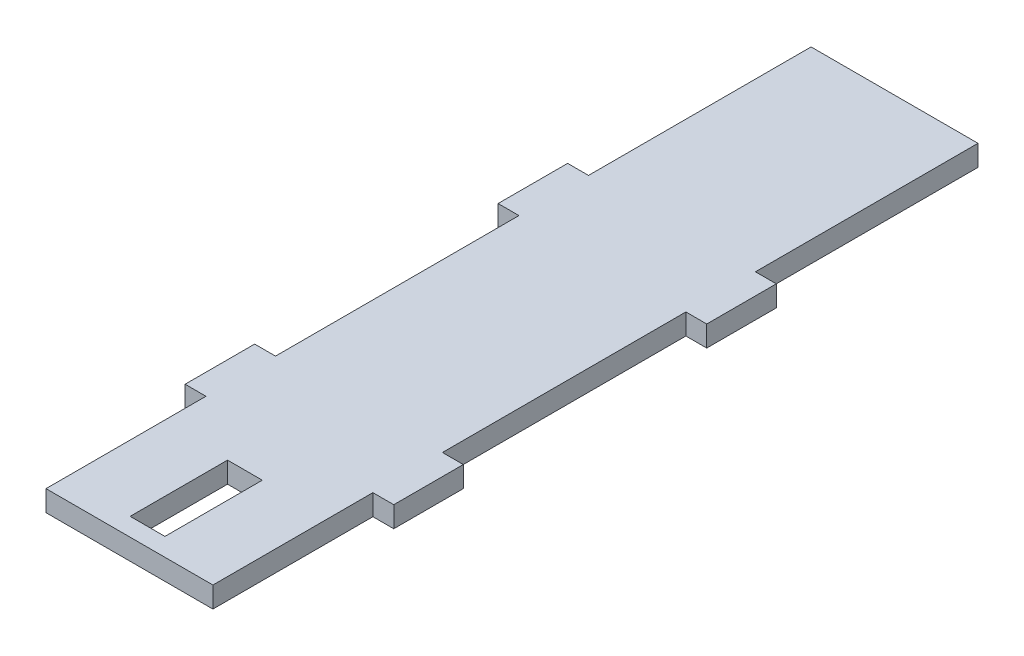
SolidWorks part; units mm, degrees
ref_plane "Спереди" through (0, 0, 0) normal (0, 0, 1) x (1, 0, 0)
ref_plane "Сверху" through (0, 0, 0) normal (0, 1, 0) x (1, 0, 0)
ref_plane "Справа" through (0, 0, 0) normal (1, 0, 0) x (0, 0, -1)
other "Configuration Table"
sketch "Эскиз1" plane through (0, 0, 0) normal (0, 1, 0) x (1, 0, 0)
  line L0 (0, -24.7852) -> (0, 24.7852) construction
  line L1 (-12, -55) -> (12, -55)
  line L2 (-12, -55) -> (-12, -32)
  line L3 (-12, 55) -> (12, 55)
  line L4 (12, -55) -> (12, -32)
  line L5 (-12, -55) -> (12, 55) construction
  line L6 (-12, 55) -> (12, -55) construction
  line L7 (12, -22) -> (15, -22)
  line L9 (12, -32) -> (15, -32)
  line L10 (15, -22) -> (15, -32)
  line L11 (-19.5061, 0) -> (19.5061, 0) construction
  line L12 (-15, -22) -> (-15, -32)
  line L13 (-12, -32) -> (-15, -32)
  line L15 (-12, -22) -> (-15, -22)
  line L16 (15, 23) -> (15, 13)
  line L17 (-12, 23) -> (-15, 23)
  line L19 (-12, 13) -> (-15, 13)
  line L20 (-15, 23) -> (-15, 13)
  line L21 (12, 13) -> (15, 13)
  line L23 (12, 23) -> (15, 23)
  line L24 (-12, 23) -> (-12, 55)
  line L25 (-12, -22) -> (-12, 13)
  line L26 (12, 23) -> (12, 55)
  line L27 (12, -22) -> (12, 13)
  point P0 (0, 0)
  point P13 (0, 0)
  point P16 (0, 0)
  dimension "D1" = 24
  dimension "D2" = 110
  dimension "D3" = 3
  dimension "D4" = 10
  dimension "D5" = 23
  dimension "D6" = 10
  dimension "D7" = 3
  dimension "D8" = 68
extrude "Бобышка-Вытянуть1" add sketch "Эскиз1" along normal blind 3
sketch "Эскиз2" plane through (0, 3, 0) normal (0, 1, 0) x (1, 0, 0)
  line L0 (-12, -55) -> (12, -55) construction
  line L1 (-2.5, -52.4) -> (2.5, -52.4)
  line L2 (-2.5, -52.4) -> (-2.5, -38.4)
  line L3 (-2.5, -38.4) -> (2.5, -38.4)
  line L4 (2.5, -52.4) -> (2.5, -38.4)
  line L5 (12, -55) -> (12, -32) construction
  dimension "D1" = 5
  dimension "D2" = 2.6
  dimension "D3" = 16.6
  dimension "D4" = 9.5
extrude "Вырез-Вытянуть1" cut sketch "Эскиз2" against normal blind 10
